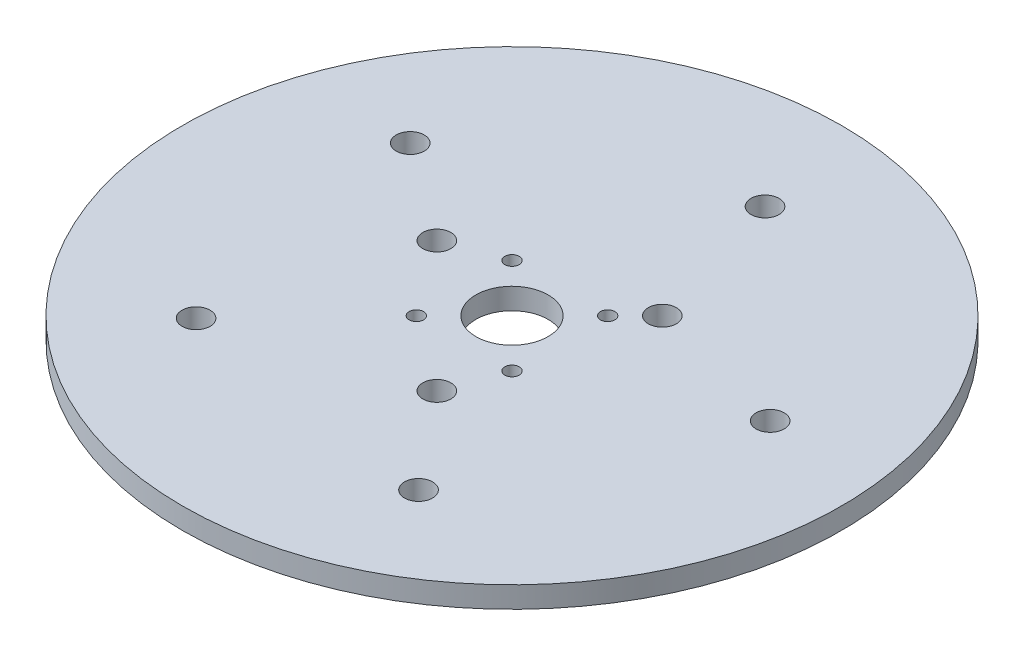
SolidWorks part; units mm, degrees
ref_plane "Front Plane" through (0, 0, 0) normal (0, 0, 1) x (1, 0, 0)
ref_plane "Top Plane" through (0, 0, 0) normal (0, 1, 0) x (1, 0, 0)
ref_plane "Right Plane" through (0, 0, 0) normal (1, 0, 0) x (0, 0, -1)
sketch "Sketch1" plane through (0, 0, 0) normal (0, 1, 0) x (1, 0, 0)
  circle A0 centre (0, 0) radius 77.5
  circle A1 centre (0, 0) radius 8.5
  dimension "D1" = 155
  dimension "D2" = 17
extrude "Body" add sketch "Sketch1" along normal blind 5
hole_wizard "M6 Clearance Hole1" positions "Sketch2" profile "Sketch3" hole size "M6" standard "ANSI Metric" end condition through all
sketch "Sketch2" plane through (0, 5, 0) normal (0, 1, 0) x (1, 0, 0)
  point P0 (7.5, 52)
  point P10 (51.7726, 8.936)
  point P11 (24.4972, -46.4773)
  point P12 (-36.6325, -37.6605)
  point P13 (-47.1373, 23.2018)
  point P15 (0, 0)
  dimension "D1" = 52
  dimension "D2" = 7.5
  dimension "D3" = 5
sketch "Sketch3" plane through (7.5, 5, -52) normal (1, 0, 0) x (0, 0, 1)
  line L0 (0, 0) -> (0, 5)
  line L1 (0, 5) -> (3.3, 5)
  line L2 (3.3, 5) -> (3.3, 0)
  line L5 (3.3, 0) -> (0, 0)
  line L11 (0, -6.35) -> (0, 107.95) construction
  dimension "Thru Hole Dia." = 6.6
  dimension "Thru Hole Depth" = 5
hole_wizard "M3 Clearance Hole1" positions "Sketch4" profile "Sketch5" hole size "M3" standard "ANSI Metric" end condition through all
sketch "Sketch4" plane through (0, 5, 0) normal (0, 1, 0) x (1, 0, 0)
  line L1 (11.25, -11.25) -> (-11.25, -11.25) construction
  line L2 (11.25, -11.25) -> (11.25, 11.25) construction
  line L3 (11.25, 11.25) -> (-11.25, 11.25) construction
  line L4 (-11.25, -11.25) -> (-11.25, 11.25) construction
  line L5 (11.25, -11.25) -> (-11.25, 11.25) construction
  line L6 (11.25, 11.25) -> (-11.25, -11.25) construction
  point P1 (0, 0)
  point P2 (-11.25, 11.25)
  point P21 (11.25, -11.25)
  point P22 (11.25, 11.25)
  point P23 (-11.25, -11.25)
  dimension "D1" = 22.5
sketch "Sketch5" plane through (0, 5, 0) normal (1, 0, 0) x (0, 0, 1)
  line L0 (0, 0) -> (0, 5)
  line L1 (0, 5) -> (1.7, 5)
  line L2 (1.7, 5) -> (1.7, 0)
  line L5 (1.7, 0) -> (0, 0)
  line L11 (0, -6.35) -> (0, 107.95) construction
  dimension "Thru Hole Dia." = 3.4
  dimension "Thru Hole Depth" = 5
hole_wizard "M6 Clearance Hole2" positions "Sketch7" profile "Sketch8" hole size "M6" standard "ANSI Metric" end condition through all
sketch "Sketch7" plane through (0, 5, 0) normal (0, 1, 0) x (1, 0, 0)
  line L0 (0, -1000) -> (0, 49000) construction
  line L1 (-707.1068, -707.1068) -> (34648.2323, 34648.2323) construction
  circle A0 centre (0, 0) radius 25 construction
  circle A1 centre (0, 0) radius 25 construction
  circle A2 centre (0, 0) radius 25 construction
  point P0 (17.6777, 17.6777)
  point P25 (6.4705, -24.1481)
  point P27 (-24.1481, 6.4705)
  point P29 (0, 0)
  dimension "D1" = 50
  dimension "D2" = 45
  dimension "D3" = 3
sketch "Sketch8" plane through (17.6777, 5, -17.6777) normal (1, 0, 0) x (0, 0, 1)
  line L0 (0, 0) -> (0, 5)
  line L1 (0, 5) -> (3.3, 5)
  line L2 (3.3, 5) -> (3.3, 0)
  line L5 (3.3, 0) -> (0, 0)
  line L11 (0, -6.35) -> (0, 107.95) construction
  dimension "Thru Hole Dia." = 6.6
  dimension "Thru Hole Depth" = 5
